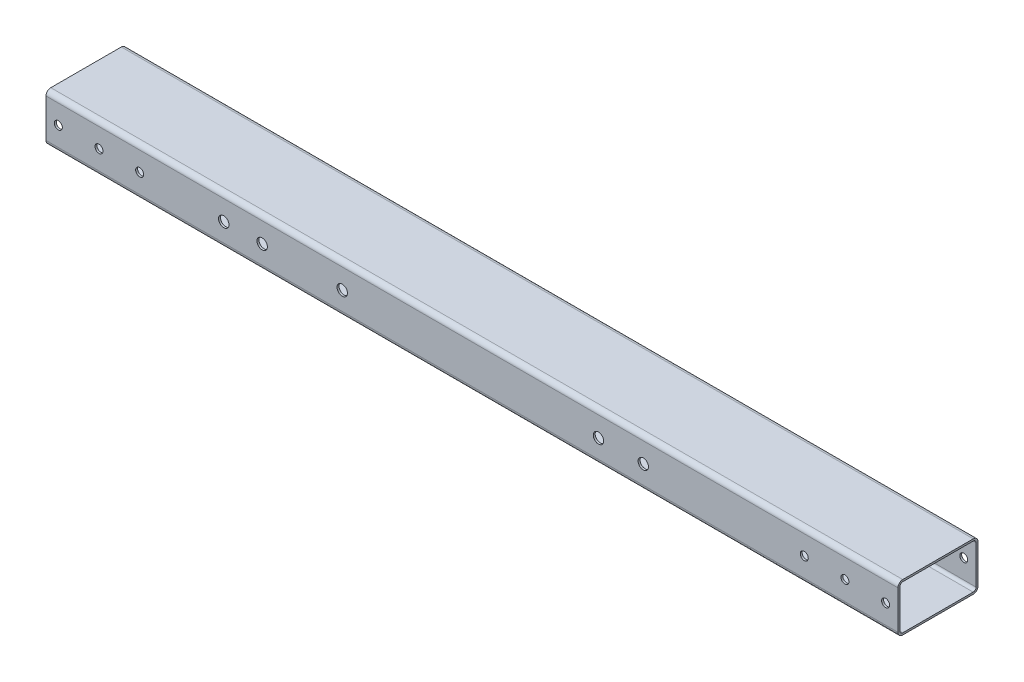
SolidWorks part; units mm, degrees
ref_plane "Plano frontal" through (0, 0, 0) normal (0, 0, 1) x (1, 0, 0)
ref_plane "Plano superior" through (0, 0, 0) normal (0, 1, 0) x (1, 0, 0)
ref_plane "Plano direito" through (0, 0, 0) normal (1, 0, 0) x (0, 0, -1)
sketch "Esboço1" plane through (0, 0, 0) normal (0, 0, 1) x (1, 0, 0)
  line L0 (0, 0) -> (532, 0)
  dimension "D1" = 532
other "Tubo retangular 50 X 30 X 2.6(1)"
ref_plane "Plano1" through (0, 0, 0) normal (1, 0, 0) x (0, 1, 0)
sketch "Sketch1" plane through (0, 0, 0) normal (1, 0, 0) x (0, 1, 0)
  line L0 (-12, -23.8) -> (12, -23.8)
  line L1 (-13.8, -22) -> (-13.8, 22)
  line L2 (12, 23.8) -> (-12, 23.8)
  line L3 (13.8, 22) -> (13.8, -22)
  line L4 (-12, -25) -> (12, -25)
  line L5 (-15, -22) -> (-15, 22)
  line L6 (12, 25) -> (-12, 25)
  line L7 (15, 22) -> (15, -22)
  arc A0 (15, 22) -> (12, 25) centre (12, 22) ccw
  arc A1 (12, -25) -> (15, -22) centre (12, -22) ccw
  arc A2 (-15, -22) -> (-12, -25) centre (-12, -22) ccw
  arc A3 (-12, 25) -> (-15, 22) centre (-12, 22) ccw
  arc A4 (-12, 23.8) -> (-13.8, 22) centre (-12, 22) ccw
  arc A5 (13.8, 22) -> (12, 23.8) centre (12, 22) ccw
  arc A6 (12, -23.8) -> (13.8, -22) centre (12, -22) ccw
  arc A7 (-13.8, -22) -> (-12, -23.8) centre (-12, -22) ccw
  point P0 (0, 25)
  point P1 (15, 0)
  point P2 (0, -25)
  point P3 (-15, 0)
  point P4 (-15, 25)
  point P5 (15, 25)
  point P6 (15, -25)
  point P7 (-15, -25)
  point P8 (0, 0)
  point P33 (0, 0)
  dimension "D1" = 3
  dimension "Thickness" = 1.2
  dimension "V_leg" = 50
  dimension "H_leg" = 30
sketch "Esboço2" plane through (0, 0, -25) normal (0, 0, -1) x (-1, 0, 0)
  line L0 (0, -12) -> (0, 12) construction
  line L1 (-58.5, 0) -> (-33.1, 0) construction
  line L2 (-33.1, 0) -> (-7.7, 0) construction
  line L3 (-7.7, 0) -> (0, 0) construction
  line L4 (-266, 15) -> (-266, -15) construction
  line L5 (-532, 15) -> (0, 15) construction
  line L6 (-532, -15) -> (0, -15) construction
  line L7 (-524.3, 0) -> (-532, 0) construction
  line L8 (-498.9, 0) -> (-524.3, 0) construction
  line L9 (-473.5, 0) -> (-498.9, 0) construction
  circle A0 centre (-58.5, 0) radius 2.5
  circle A1 centre (-33.1, 0) radius 2.5
  circle A2 centre (-7.7, 0) radius 2.5
  circle A6 centre (-524.3, 0) radius 2.5
  circle A7 centre (-498.9, 0) radius 2.5
  circle A8 centre (-473.5, 0) radius 2.5
  dimension "D1" = 7.7
  dimension "D2" = 25.4
  dimension "D3" = 25.4
  dimension "D4" = 5
  dimension "D5" = 5
  dimension "D6" = 5
extrude "Corte-extrusão1" cut sketch "Esboço2" against normal through all
sketch "Esboço3" plane through (0, 0, -25) normal (0, 0, -1) x (-1, 0, 0)
  circle A0 centre (-185, -0.5) radius 3.25
  circle A1 centre (-111, -0.5) radius 3.25
  circle A2 centre (-373, -0.5) radius 3.25
extrude "Corte-extrusão2" cut sketch "Esboço3" against normal through all
sketch "Esboço4" plane through (0, 0, -25) normal (0, 0, -1) x (-1, 0, 0)
  circle A0 centre (-345, -0.5) radius 3.25
  circle A1 centre (-135, -0.5) radius 3.25
extrude "Corte-extrusão3" cut sketch "Esboço4" against normal through all
